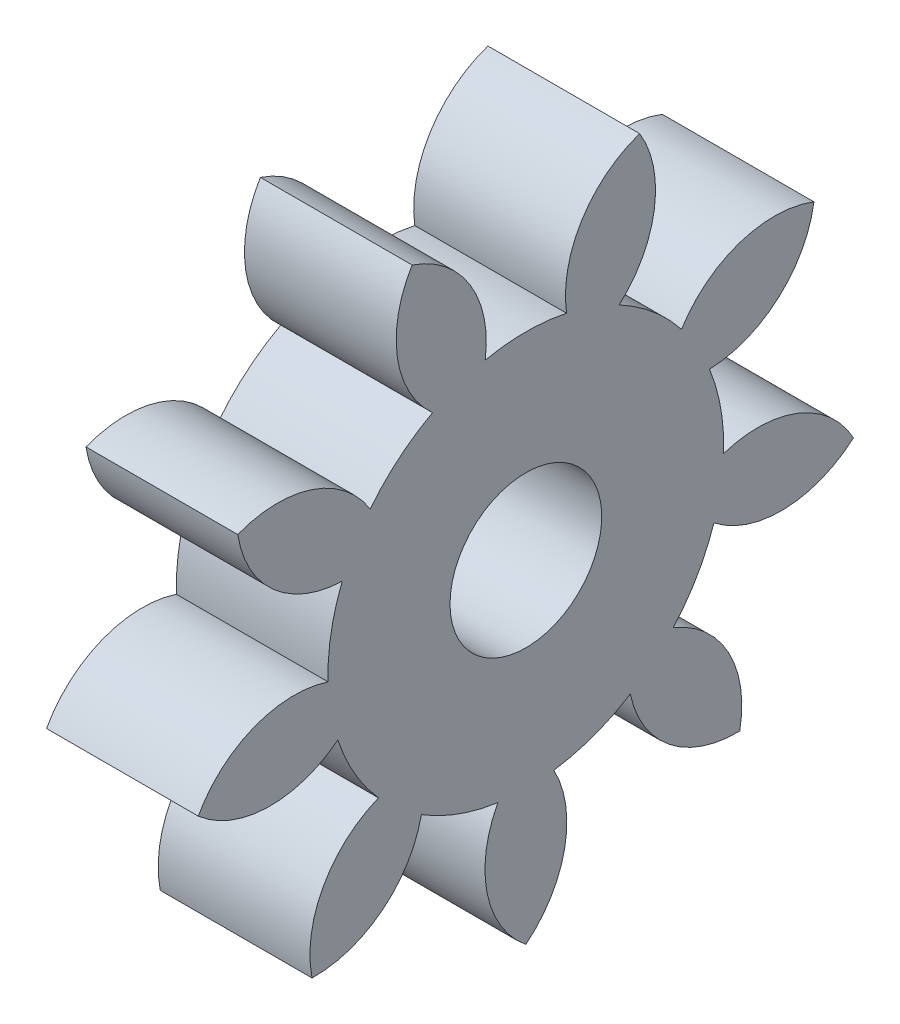
SolidWorks part; units mm, degrees
ref_plane "Plane1" through (0, 0, 0) normal (0, 0, 1) x (1, 0, 0)
ref_plane "Plane2" through (0, 0, 0) normal (0, 1, 0) x (1, 0, 0)
ref_plane "Plane3" through (0, 0, 0) normal (1, 0, 0) x (0, 0, -1)
sketch "HoldingSke" plane through (0, 0, 0) normal (0, 1, 0) x (1, 0, 0)
  line L0 (0, 0) -> (500.2823, -88.2133)
  line L1 (-15, 0) -> (100, 0) construction
  line L2 (0, 0) -> (-2.1039, 2.3779)
  line L3 (0, 0) -> (-11.863, 4.5341)
  line L4 (0, 0) -> (8.5048, 1.4996)
  line L5 (0, 0) -> (-47.5972, -17.7524)
  line L6 (0, 0) -> (-2.632, -1.7758)
  line L7 (-2.1039, 2.3779) -> (8.8308, 51.9871)
  line L8 (-76.2, 54.61) -> (-72.771, 54.61)
  line L9 (-71.009, 38.7566) -> (-53.1078, 45.2721)
  line L10 (-76.2, 71.12) -> (104.1128, 71.12)
  line L11 (0, 0) -> (-3.175, 0)
  line L12 (-76.2, 101.6) -> (-76.1492, 101.6)
  line L13 (24.9733, 27.94) -> (52.9518, 28.4284)
  line L14 (24.9733, 27.94) -> (25.0241, 27.9398)
  line L15 (24.9733, 27.94) -> (100.4021, 29.52)
  circle A0 centre (0, 0) radius 1.5875
  circle A1 centre (0, 0) radius 4.1402
  circle A2 centre (0, 0) radius 38.1
  circle A3 centre (0, 0) radius 1.5875
  dimension "MHD" = 8.2804
  dimension "Hub_dia" = 76.2
  dimension "Bore" = 3.175
  dimension "MBD" = 3.175
  dimension "Num_teeth" = 10
  dimension "Pitch_radius" = 180.3128
  dimension "Pitch" = 508
  dimension "Width" = 3.175
  dimension "Overall_len" = 50.8
  dimension "Show_teeth" = 10
  dimension "Thickness" = 3.175
  dimension "OAL" = 50.8001
  dimension "T_dim" = 3.429
  dimension "Ap" = 20
  dimension "H" = 19.05
  dimension "Backlash" = 0.0508
  dimension "Addendum_fac" = 1
  dimension "Dedendum_fac" = 1.2
  dimension "Clearance_fac" = 0.2
  dimension "Dedendum_add" = 0.0508
sketch "BasProSke" plane through (0, 0, 0) normal (0, 1, 0) x (1, 0, 0)
  line L0 (-10, 0) -> (60, 0) construction
  line L1 (0, 0) -> (0, 6.985)
  line L2 (0, 0) -> (3.175, 0)
  line L3 (3.175, 0) -> (3.175, 6.985)
  line L4 (3.175, 6.985) -> (0, 6.985)
  dimension "Diameter" = 13.97
  dimension "Thickness" = 3.175
revolve "Base-Revolve" add sketch "BasProSke" angle 360 about L0
sketch "TooCutSke" plane through (0, 0, 0) normal (1, 0, 0) x (0, 0, -1)
  line L1 (0, 0) -> (0, 107) construction
  line L2 (0, 0) -> (-1.1786, 5.5922) construction
  line L3 (0, 0) -> (-3.8703, 10.6336) construction
  line L4 (-1.1786, 5.5922) -> (-1.9352, 5.3168) construction
  arc A0 (0.8509, 4.0518) -> (-0.8509, 4.0518) centre (0, 0) ccw
  arc A1 (2.4581, 6.5653) -> (-2.4581, 6.5653) centre (0, 0) ccw
  circle A2 centre (0, 0) radius 5.715 construction
  circle A3 centre (0, 0) radius 5.3703 construction
  arc A4 (-0.8509, 4.0518) -> (-2.4581, 6.5653) centre (-3.1139, 4.3754) ccw
  arc A5 (2.4581, 6.5653) -> (0.8509, 4.0518) centre (3.1139, 4.3754) ccw
  dimension "Root_dia" = 8.2804
  dimension "Overcut_dia" = 14.0208
  dimension "Pitch_dia" = 11.43
  dimension "Base_dia" = 10.7407
  dimension "Flank_rad" = 2.286
  dimension "Half_ang" = 20
  dimension "Half_CT" = 0.8051
extrude "ToothCut" cut sketch "TooCutSke" along normal through all
fillet "Breaks" [suppressed] radius 0.0254
fillet "RootFillets" [suppressed] radius 0.3048
pattern_circular "TeethCuts" count 10 every 40 about axis through (-10, 0, 0) along (1, 0, 0) of "ToothCut"
sketch "HubNeaOneSke" plane through (0, 0, 0) normal (-1, 0, 0) x (0, 0, 1)
  circle A0 centre (0, 0) radius 4.1402
  dimension "Diameter" = 8.2804
extrude "HubNearOne" [suppressed] add sketch "HubNeaOneSke" along normal blind 47.6251
sketch "HubNeaBotSke" plane through (0, 0, 0) normal (-1, 0, 0) x (0, 0, 1)
  circle A0 centre (0, 0) radius 4.1402
  dimension "Diameter" = 8.2804
extrude "HubNearBoth" [suppressed] add sketch "HubNeaBotSke" along normal blind 23.8125
ref_plane "FarPln" through (3.175, 0, 0) normal (1, 0, 0) x (0, 0, -1)
sketch "HubFarSke" plane through (3.175, 0, 0) normal (1, 0, 0) x (0, 0, -1)
  circle A0 centre (0, 0) radius 4.1402
  dimension "Diameter" = 8.2804
extrude "HubFar" [suppressed] add sketch "HubFarSke" along normal blind 23.8125
sketch "BorSke" plane through (0, 0, 0) normal (1, 0, 0) x (0, 0, -1)
  circle A0 centre (0, 0) radius 1.5875
  dimension "Diameter" = 3.175
extrude "Bore" cut sketch "BorSke" along normal mid plane 101.6001
sketch "KeySke" plane through (0, 0, 0) normal (1, 0, 0) x (0, 0, -1)
  line L0 (-0.127, 0) -> (-0.127, 1.8415)
  line L1 (-0.127, 1.8415) -> (0.127, 1.8415)
  line L2 (0.127, 1.8415) -> (0.127, 0)
  line L3 (0, 0) -> (0, 34) construction
  line L4 (-0.127, 0) -> (0.127, 0)
  dimension "Offset" = 1.8415
  dimension "Width" = 0.254
extrude "Keyway" [suppressed] cut sketch "KeySke" along normal mid plane 101.6001
pattern_circular "Keyway2" [suppressed] count 2 every 90 about axis through (-10, 0, 0) along (1, 0, 0)
equation "' \"Pitch@HoldingSke\" = 4"
equation "' \"Num_teeth@HoldingSke\" = 12"
equation "' \"Ap@HoldingSke\" =  20"
equation "' \"Width@HoldingSke\" = 0.5"
equation "' \"Hub_dia@HoldingSke\"= 1"
equation "' \"Overall_len@HoldingSke\" = 1.0"
equation "' \"Bore@HoldingSke\" = 0.75"
equation "' \"T_dim@HoldingSke\" = 0.85"
equation "' \"Width@KeySke\" = 0.25"
equation "' \"Show_teeth@HoldingSke\" = 13"
equation "' \"Backlash@HoldingSke\" = 0.009"
equation "' \"Addendum_fac@HoldingSke\" = 1.0"
equation "' \"Dedendum_fac@HoldingSke\" = 1.25"
equation "' \"Dedendum_add@HoldingSke\" = 0.00005"
equation "' \"Clearance_fac@HoldingSke\" = 0.25"
equation "' \"Pitch@HoldingSke\" = 0.5"
equation "' \"Num_teeth@HoldingSke\" = 23"
equation "' \"Show_teeth@HoldingSke\" = 23"
equation "' \"Backlash@HoldingSke\" = 0.0375"
equation "\"Overcut_dia@TooCutSke\"=(9 + 2 * \"Addendum_fac@HoldingSke\") / \"Pitch@HoldingSke\" + 0.002"
equation "\"Pitch_dia@TooCutSke\"=9/ \"Pitch@HoldingSke\""
equation "\"Base_dia@TooCutSke\"=9 / \"Pitch@HoldingSke\" * cos((\"Ap@HoldingSke\"  * 3.14159265 / 180))"
equation "\"Root_dia@TooCutSke\"=(9 + 2) / \"Pitch@HoldingSke\" - 2 * (\"Addendum_fac@HoldingSke\" + \"Dedendum_fac@HoldingSke\") / \"Pitch@HoldingSke\" - \"Dedendum_add@HoldingSke\" * 2"
equation "\"Half_ang@TooCutSke\"=180 / 9"
equation "\"Half_CT@TooCutSke\"=9 / \"Pitch@HoldingSke\" * sin((3.14159265 / 2 / \"Num_teeth@HoldingSke\")) / 2 - 7 * \"Backlash@HoldingSke\" / 4"
equation "\"Flank_rad@TooCutSke\"=9/ \"Pitch@HoldingSke\" / 5"
equation "\"Radius@RootFillets\" = \"Clearance_fac@HoldingSke\" / \"Pitch@HoldingSke\" + \"Dedendum_add@HoldingSke\""
equation "\"Break_rad@Breaks\" = 0.02 / \"Pitch@HoldingSke\""
equation "\"Thickness@HoldingSke\" = \"Width@HoldingSke\""
equation "\"OAL@HoldingSke\" = \"Thickness@HoldingSke\""
equation "\"MHD@HoldingSke\" = (\"Num_teeth@HoldingSke\" + 2) / \"Pitch@HoldingSke\" - 2 * (\"Addendum_fac@HoldingSke\" + \"Dedendum_fac@HoldingSke\")  / \"Pitch@HoldingSke\" - \"Dedendum_add@HoldingSke\" * 2"
equation "\"MBD@HoldingSke\" = (\"Num_teeth@HoldingSke\" + 2) / \"Pitch@HoldingSke\" - 2 * (\"Addendum_fac@HoldingSke\" + \"Dedendum_fac@HoldingSke\")  / \"Pitch@HoldingSke\" - \"Dedendum_add@HoldingSke\" * 2 - 0.002"
equation "\"MHD@HoldingSke\" = ((sgn( \"MHD@HoldingSke\" - \"Hub_dia@HoldingSke\" )-1)*( \"MHD@HoldingSke\" - \"Hub_dia@HoldingSke\" ))/-2+ \"Hub_dia@HoldingSke\""
equation "\"MBD@HoldingSke\" = ((sgn( \"MBD@HoldingSke\" - \"Bore@HoldingSke\" )-1)*( \"MBD@HoldingSke\" - \"Bore@HoldingSke\" ))/-2+ \"Bore@HoldingSke\""
equation "\"OAL@HoldingSke\" = ((sgn( \"OAL@HoldingSke\" - \"Overall_len@HoldingSke\" )+1)*( \"OAL@HoldingSke\" - \"Overall_len@HoldingSke\" ))/2 + \"Overall_len@HoldingSke\" + 0.000002"
equation "\"Num_teeth@TeethCuts\"=int( 9 ) + 1"
equation "\"Num_teeth@TeethCuts\" = ((sgn( \"Num_teeth@TeethCuts\" - \"Num_teeth@HoldingSke\" )-1)*( \"Num_teeth@TeethCuts\" - \"Num_teeth@HoldingSke\" ))/-2+ \"Num_teeth@HoldingSke\""
equation "\"Num_teeth@TeethCuts\" = ((sgn( \"Num_teeth@TeethCuts\" - 2.0)+1)*( \"Num_teeth@TeethCuts\" - 2.0))/2 +2.0"
equation "\"Angle@TeethCuts\"=360.0 / 9"
equation "\"Diameter@BasProSke\"=(9 + 2 * \"Addendum_fac@HoldingSke\") / \"Pitch@HoldingSke\""
equation "\"Thickness@BasProSke\"  = \"Thickness@HoldingSke\""
equation "' \"Fillet_rad@BasProSke\" =  \"Thickness@HoldingSke\" * 0.05"
equation "\"MHD@HoldingSke\" = ((sgn( \"MHD@HoldingSke\" - \"Root_dia@TooCutSke\" )-1)*( \"MHD@HoldingSke\" - \"Root_dia@TooCutSke\" ))/-2+ \"Root_dia@TooCutSke\""
equation "\"Diameter@HubNeaOneSke\" = \"MHD@HoldingSke\""
equation "\"Length@HubNearOne\" = \"OAL@HoldingSke\" - \"Thickness@BasProSke\""
equation "\"Diameter@HubNeaBotSke\" = \"MHD@HoldingSke\""
equation "\"Length@HubNearBoth\" = ( \"OAL@HoldingSke\" - \"Thickness@BasProSke\" ) / 2.0"
equation "\"Thickness@FarPln\" = \"Thickness@BasProSke\""
equation "\"Diameter@HubFarSke\" = \"MHD@HoldingSke\""
equation "\"Length@HubFar\" = ( \"OAL@HoldingSke\" - \"Thickness@BasProSke\" ) / 2.0"
equation "\"Diameter@BorSke\" = \"MBD@HoldingSke\""
equation "\"D1@Bore\" = \"OAL@HoldingSke\" * 2.0"
equation "\"D1@Keyway\" = \"OAL@HoldingSke\" * 2.0"
equation "\"Offset@KeySke\" = \"T_dim@HoldingSke\" - \"MBD@HoldingSke\" / 2.0"
